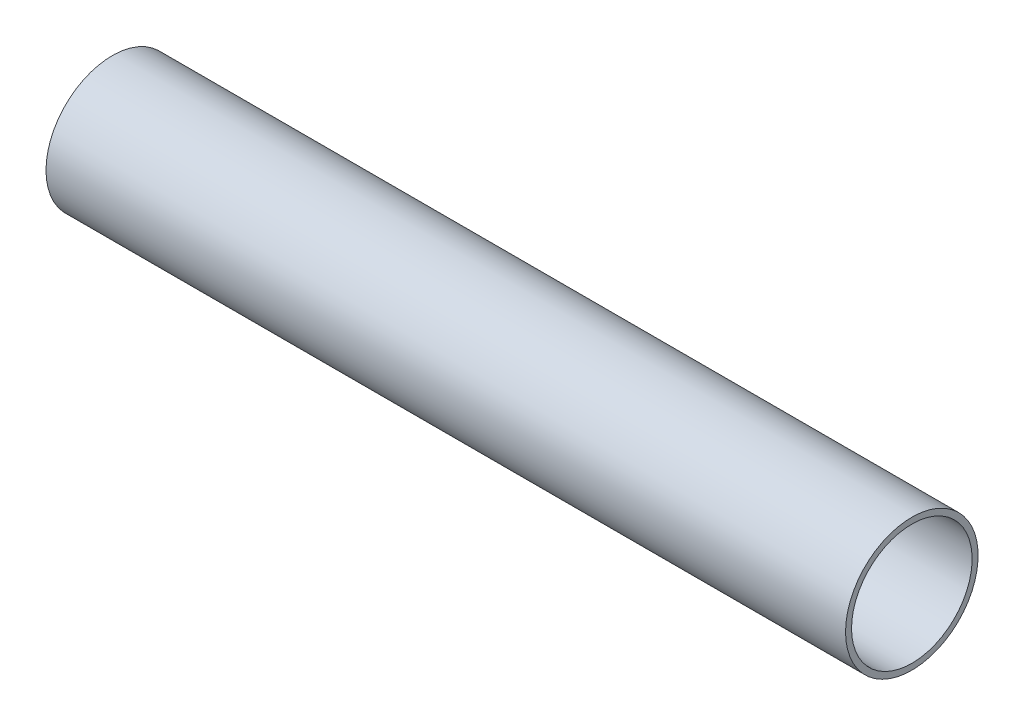
SolidWorks part; units mm, degrees
material "Thornel Mat VMA"
ref_plane "Front Plane" through (0, 0, 0) normal (0, 0, 1) x (1, 0, 0)
ref_plane "Top Plane" through (0, 0, 0) normal (0, 1, 0) x (1, 0, 0)
ref_plane "Right Plane" through (0, 0, 0) normal (1, 0, 0) x (0, 0, -1)
sketch "Sketch1" plane through (0, 0, 0) normal (1, 0, 0) x (0, 0, -1)
  circle A0 centre (0, 0) radius 11.4935
  circle A1 centre (0, 0) radius 12.6365
  dimension "D1" = 22.987
  dimension "D2" = 1.143
extrude "Boss-Extrude1" add sketch "Sketch1" along normal mid plane 152.4
